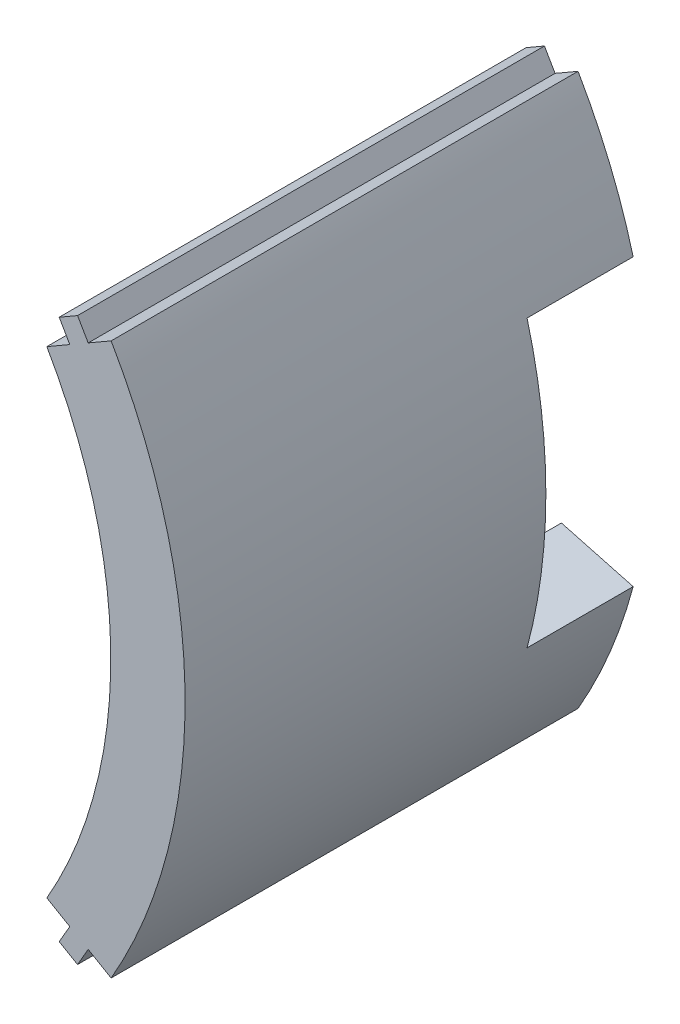
SolidWorks part; units mm, degrees
ref_plane "Спереди" through (0, 0, 0) normal (0, 0, 1) x (1, 0, 0)
ref_plane "Сверху" through (0, 0, 0) normal (0, 1, 0) x (1, 0, 0)
ref_plane "Справа" through (0, 0, 0) normal (1, 0, 0) x (0, 0, -1)
sketch "Эскиз1" plane through (0, 0, 0) normal (0, 0, 1) x (1, 0, 0)
  line L0 (0, 0) -> (0, 57.8819) construction
  line L1 (0, 0) -> (171.1762, 0) construction
  line L2 (0, 0) -> (145.7194, 84.1311) construction
  line L3 (19.4856, 11.25) -> (22.5167, 13)
  line L4 (19.4856, -11.25) -> (22.5167, -13)
  arc A0 (19.4856, -11.25) -> (19.4856, 11.25) centre (0, 0) ccw
  arc A1 (22.5167, -13) -> (22.5167, 13) centre (0, 0) ccw
  dimension "D2" = 52
  dimension "D3" = 45
  dimension "D1" = 30
extrude "Бобышка-Вытянуть1" add sketch "Эскиз1" along normal blind 22
sketch "Эскиз2" plane through (0, 0, 0) normal (-0.5, -0.866, 0) x (0.866, -0.5, 0)
  line L0 (24.25, 22) -> (24.25, 0) construction
  line L1 (22.5, 22) -> (26, 22) construction
  line L2 (22.5, 0) -> (26, 0) construction
  line L3 (23.75, 22) -> (24.75, 22)
  line L4 (24.75, 22) -> (24.75, 0)
  line L5 (24.75, 0) -> (23.75, 0)
  line L6 (23.75, 22) -> (23.75, 0)
  dimension "D1" = 0.5
sketch "Эскиз4" plane through (0, 0, 0) normal (-0.5, 0.866, 0) x (-0.866, -0.5, 0)
  line L0 (-24.25, 22) -> (-24.25, 0) construction
  line L3 (-24.75, 22) -> (-23.75, 22)
  line L4 (-23.75, 22) -> (-23.75, 0)
  line L5 (-23.75, 0) -> (-24.75, 0)
  line L6 (-24.75, 22) -> (-24.75, 0)
  line L7 (-26, 22) -> (-22.5, 22) construction
  line L8 (-26, 0) -> (-22.5, 0) construction
  point P3 (-24.25, 22)
  point P4 (-24.25, 0)
  dimension "D1" = 0.5
extrude "Бобышка-Вытянуть2" add sketch "Эскиз4" along normal blind 1 contours L6 L5 L4 L3
extrude "Бобышка-Вытянуть3" add sketch "Эскиз2" along normal blind 1 contours L6 L5 L4 L3
sketch "Эскиз6" plane through (0, 0, 0) normal (0, 0, -1) x (-1, 0, 0)
  line L0 (0, 0) -> (-46.585, 0) construction
  line L1 (0, 0) -> (-46.0133, 12.3292) construction
  line L2 (-21.7333, 5.8234) -> (-25.1141, 6.7293)
  line L3 (-21.7333, -5.8234) -> (-25.1141, -6.7293)
  arc A0 (-25.1141, 6.7293) -> (-25.1141, -6.7293) centre (0, 0) ccw
  arc A1 (-22.5167, 13) -> (-22.5167, -13) centre (0, 0) ccw construction
  arc A2 (-21.7333, 5.8234) -> (-21.7333, -5.8234) centre (0, 0) ccw
  arc A3 (-19.4856, 11.25) -> (-19.4856, -11.25) centre (0, 0) ccw construction
  dimension "D1" = 15
extrude "Вырез-Вытянуть2" cut sketch "Эскиз6" against normal blind 5
